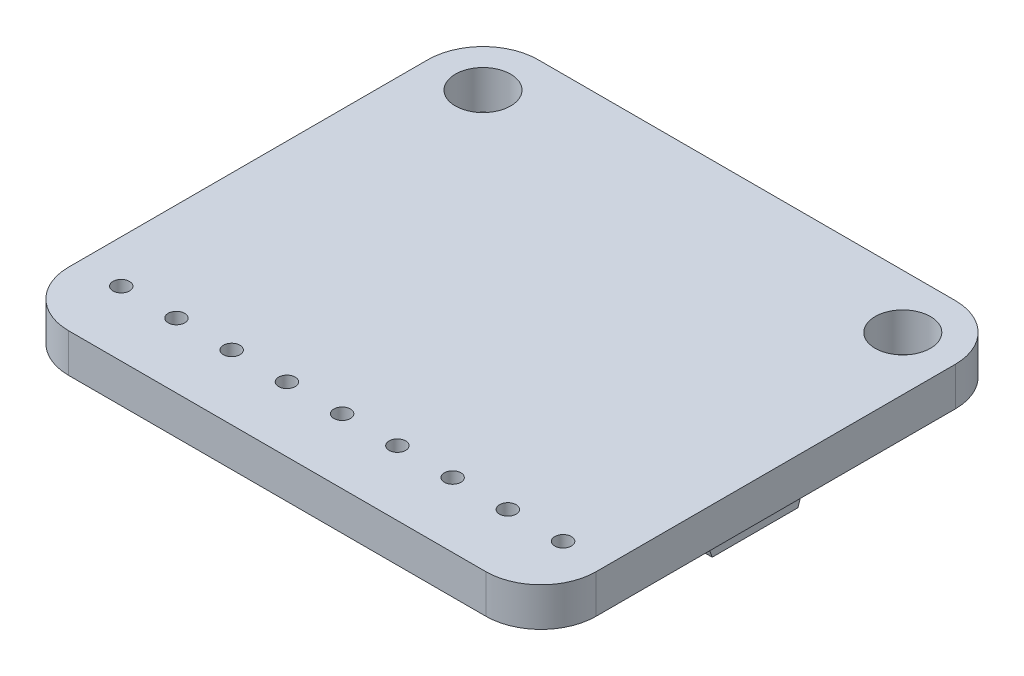
SolidWorks part; units mm, degrees
ref_plane "Front Plane" through (0, 0, 0) normal (0, 0, 1) x (1, 0, 0)
ref_plane "Top Plane" through (0, 0, 0) normal (0, 1, 0) x (1, 0, 0)
ref_plane "Right Plane" through (0, 0, 0) normal (1, 0, 0) x (0, 0, -1)
sketch "Sketch1" plane through (0, 0, 0) normal (0, 1, 0) x (1, 0, 0)
  line L1 (9.5885, 10.795) -> (-9.5885, 10.795)
  line L2 (12.1285, 8.255) -> (12.1285, -8.255)
  line L3 (9.5885, -10.795) -> (-9.5885, -10.795)
  line L4 (-12.1285, 8.255) -> (-12.1285, -8.255)
  line L5 (12.1285, 10.795) -> (-12.1285, -10.795) construction
  line L6 (12.1285, -10.795) -> (-12.1285, 10.795) construction
  line L14 (0, 0) -> (0, 10.4198) construction
  line L15 (-9.5885, 8.255) -> (9.5885, -8.255) construction
  line L16 (9.5885, 8.255) -> (-9.5885, -8.255) construction
  line L17 (0, 0) -> (-8.3012, 0) construction
  arc A0 (9.5885, 10.795) -> (12.1285, 8.255) centre (9.5885, 8.255) cw
  arc A1 (12.1285, -8.255) -> (9.5885, -10.795) centre (9.5885, -8.255) cw
  arc A2 (-9.5885, -10.795) -> (-12.1285, -8.255) centre (-9.5885, -8.255) cw
  arc A3 (-9.5885, 10.795) -> (-12.1285, 8.255) centre (-9.5885, 8.255) ccw
  circle A8 centre (-9.652, 8.3185) radius 1.27
  circle A9 centre (9.652, 8.3185) radius 1.27
  point P0 (0, 0)
  point P18 (0, 0)
  point P36 (0, 0)
  dimension "D1" = 2.54
  dimension "D9" = 2.54
  dimension "D4" = 2.4765
  dimension "D2" = 21.59
  dimension "D3" = 24.257
  dimension "D5" = 2.4765
extrude "Boss-Extrude1" add sketch "Sketch1" along normal blind 1.778
sketch "Sketch2" plane through (0, 0, 0) normal (0, -1, 0) x (1, 0, 0)
  line L0 (-9.5885, 10.795) -> (9.5885, 10.795) construction
  line L1 (-6.604, 9.144) -> (6.604, 9.144)
  line L2 (-6.604, 9.144) -> (-6.604, 6.477)
  line L3 (-6.604, 6.477) -> (6.604, 6.477)
  line L4 (6.604, 9.144) -> (6.604, 6.477)
  line L5 (0, 0) -> (0, 2.4773) construction
  point P9 (0, 0)
  dimension "D1" = 13.208
  dimension "D2" = 2.667
  dimension "D3" = 1.651
extrude "Boss-Extrude2" add sketch "Sketch2" along normal blind 2.159
sketch "Sketch3" plane through (0, -2.159, 0) normal (0, -1, 0) x (1, 0, 0)
  line L0 (-6.604, 7.8105) -> (6.604, 7.8105) construction
  line L1 (-6.604, 9.144) -> (-6.604, 6.477) construction
  line L2 (6.604, 6.477) -> (6.604, 9.144) construction
  line L3 (0, 0) -> (0, 11.811) construction
  circle A0 centre (-10.16, 7.8105) radius 0.381
  circle A1 centre (-7.62, 7.8105) radius 0.381
  circle A2 centre (-5.08, 7.8105) radius 0.381
  circle A3 centre (7.62, 7.8105) radius 0.381
  circle A4 centre (10.16, 7.8105) radius 0.381
  circle A5 centre (-2.54, 7.8105) radius 0.381
  circle A6 centre (2.54, 7.8105) radius 0.381
  circle A7 centre (5.08, 7.8105) radius 0.381
  circle A8 centre (0, 7.8105) radius 0.381
  dimension "D2" = 2.54
  dimension "D3" = 0.762
  dimension "D1" = 2.54
  dimension "D4" = 2.54
  dimension "D5" = 2.54
extrude "Cut-Extrude1" cut sketch "Sketch3" against normal through all
sketch "Sketch4" plane through (-12.1285, 0, 0) normal (-1, 0, 0) x (0, 0, 1)
  line L0 (-8.255, 0) -> (8.255, 0) construction
  line L1 (3.3678, 0) -> (11.6921, 0)
  line L2 (3.3678, 0) -> (3.3678, -3.5374)
  line L3 (3.3678, -3.5374) -> (11.6921, -3.5374)
  line L4 (11.6921, 0) -> (11.6921, -3.5374)
  point P6 (11.6921, -3.5374)
extrude "Cut-Extrude2" cut sketch "Sketch4" against normal through all
sketch "Sketch5" plane through (0, 0, 0) normal (0, -1, 0) x (1, 0, 0)
  text T0 "MAX31856"
  point P1 (-5.8803, -4.4852)
  point P2 (-6.2454, -7.5883)
extrude "Cut-Extrude3" cut sketch "Sketch5" against normal blind 0.0254
sketch "Sketch7" plane through (0, 0, 0) normal (0, -1, 0) x (1, 0, 0)
  line L0 (0, 0) -> (0, 4.9703) construction
  line L1 (-3.81, -3.937) -> (3.81, -3.937)
  line L2 (-3.81, -3.937) -> (-3.81, -10.795)
  line L3 (-3.81, -10.795) -> (3.81, -10.795)
  line L4 (3.81, -3.937) -> (3.81, -10.795)
  line L5 (9.5885, -10.795) -> (-9.5885, -10.795) construction
  dimension "D1" = 6.858
  dimension "D2" = 7.62
extrude "Boss-Extrude3" add sketch "Sketch7" along normal blind 8.636
sketch "Sketch8" plane through (-3.81, 0, 0) normal (-1, 0, 0) x (0, 0, 1)
  line L0 (-10.795, -4.572) -> (-9.3345, -8.636)
  line L1 (-10.795, -8.636) -> (-10.795, 0) construction
  line L2 (-3.937, -8.636) -> (-10.795, -8.636) construction
  line L3 (-3.937, -4.572) -> (-5.3975, -8.636)
  line L4 (-3.937, -8.636) -> (-3.937, 0) construction
  line L5 (-7.366, -8.636) -> (-7.366, -4.1161) construction
  line L6 (-10.795, -4.572) -> (-10.795, -8.636)
  line L7 (-10.795, -8.636) -> (-9.3345, -8.636)
  line L8 (-3.937, -4.572) -> (-3.937, -8.636)
  line L9 (-3.937, -8.636) -> (-5.3975, -8.636)
  line L10 (-3.937, 0) -> (-10.795, 0) construction
  dimension "D1" = 4.572
  dimension "D2" = 3.937
extrude "Cut-Extrude4" cut sketch "Sketch8" against normal through all
